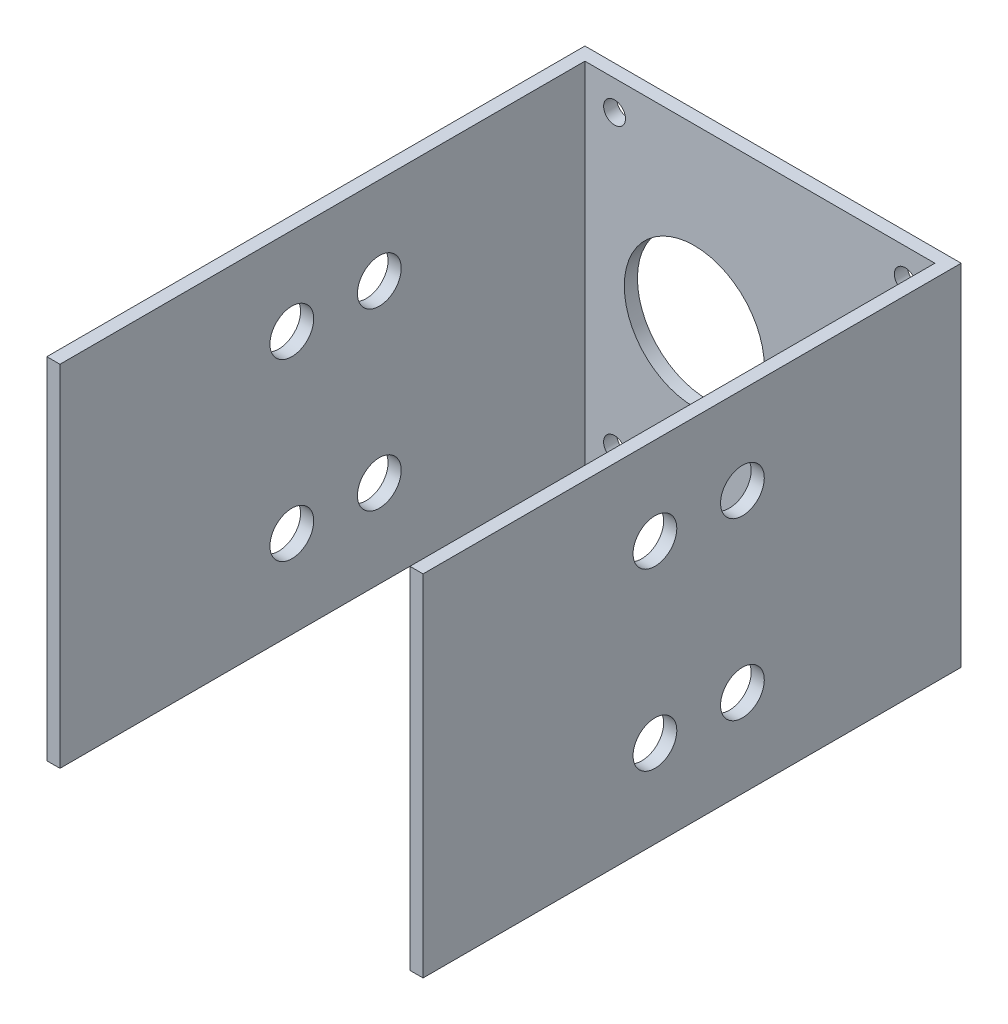
SolidWorks part; units mm, degrees
ref_plane "Front Plane" through (0, 0, 0) normal (0, 0, 1) x (1, 0, 0)
ref_plane "Top Plane" through (0, 0, 0) normal (0, 1, 0) x (1, 0, 0)
ref_plane "Right Plane" through (0, 0, 0) normal (1, 0, 0) x (0, 0, -1)
sketch "Sketch1" plane through (0, 0, 0) normal (0, 0, 1) x (1, 0, 0)
  line L1 (-43, 40) -> (43, 40)
  line L2 (-43, 40) -> (-43, -40)
  line L3 (-43, -40) -> (43, -40)
  line L4 (43, 40) -> (43, -40)
  line L5 (-43, 40) -> (43, -40) construction
  line L6 (-43, -40) -> (43, 40) construction
  point P0 (0, 0)
  dimension "D1" = 86
  dimension "D2" = 80
extrude "Boss-Extrude1" add sketch "Sketch1" along normal blind 3
sketch "Sketch2" plane through (0, 0, 3) normal (0, 0, 1) x (1, 0, 0)
  line L0 (-43, 40) -> (-40, 40)
  line L1 (43, 40) -> (-43, 40) construction
  line L2 (-40, 40) -> (-40, -40)
  line L3 (-43, -40) -> (43, -40) construction
  line L4 (-40, -40) -> (-43, -40)
  line L5 (-43, -40) -> (-43, 40)
  line L6 (43, 40) -> (40, 40)
  line L7 (40, 40) -> (40, -40)
  line L8 (40, -40) -> (43, -40)
  line L9 (43, -40) -> (43, 40)
  dimension "D1" = 3
  dimension "D2" = 3
extrude "Boss-Extrude2" add sketch "Sketch2" along normal blind 120 contours L5 L0 L2 L4 | L9 L6 L7 L8
sketch "Sketch3" plane through (0, 0, 0) normal (0, 0, -1) x (-1, 0, 0)
  line L1 (43, -40) -> (-43, -40) construction
  line L3 (43, 40) -> (43, -40) construction
  circle A0 centre (15, 0) radius 16
  dimension "D1" = 32
  dimension "D2" = 28
  dimension "D3" = 40
extrude "Cut-Extrude1" cut sketch "Sketch3" against normal blind 120
sketch "Sketch4" plane through (0, 0, 0) normal (0, 0, -1) x (-1, 0, 0)
  line L0 (-43, -40) -> (-43, 40) construction
  line L1 (-43, 40) -> (43, 40) construction
  line L2 (43, 40) -> (43, -40) construction
  line L3 (43, -40) -> (-43, -40) construction
  circle A0 centre (-33.23, 33.23) radius 2.5
  circle A1 centre (-33.23, -33.23) radius 2.5
  circle A2 centre (33.23, -33.23) radius 2.5
  circle A3 centre (33.23, 33.23) radius 2.5
  dimension "D1" = 5
  dimension "D2" = 9.77
  dimension "D3" = 6.77
  dimension "D4" = 9.77
  dimension "D5" = 9.77
  dimension "D6" = 9.77
  dimension "D7" = 6.77
  dimension "D8" = 6.77
  dimension "D9" = 6.77
extrude "Cut-Extrude2" cut sketch "Sketch4" against normal blind 120
sketch "Sketch5" plane through (43, 0, 0) normal (1, 0, 0) x (0, 0, -1)
  line L1 (-123, 40) -> (0, 40) construction
  line L2 (0, -40) -> (0, 40) construction
  circle A0 centre (-50, 20) radius 5
  circle A1 centre (-50, -20) radius 5
  circle A2 centre (-70, 20) radius 5
  circle A3 centre (-70, -20) radius 5
  point P8 (0, 0)
  point P9 (0, 0)
  point P10 (0, 0)
  dimension "D1" = 10
  dimension "D2" = 20
  dimension "D3" = 20
  dimension "D4" = 50
  dimension "D6" = 40
  dimension "D7" = 20
extrude "Cut-Extrude3" cut sketch "Sketch5" against normal through all
